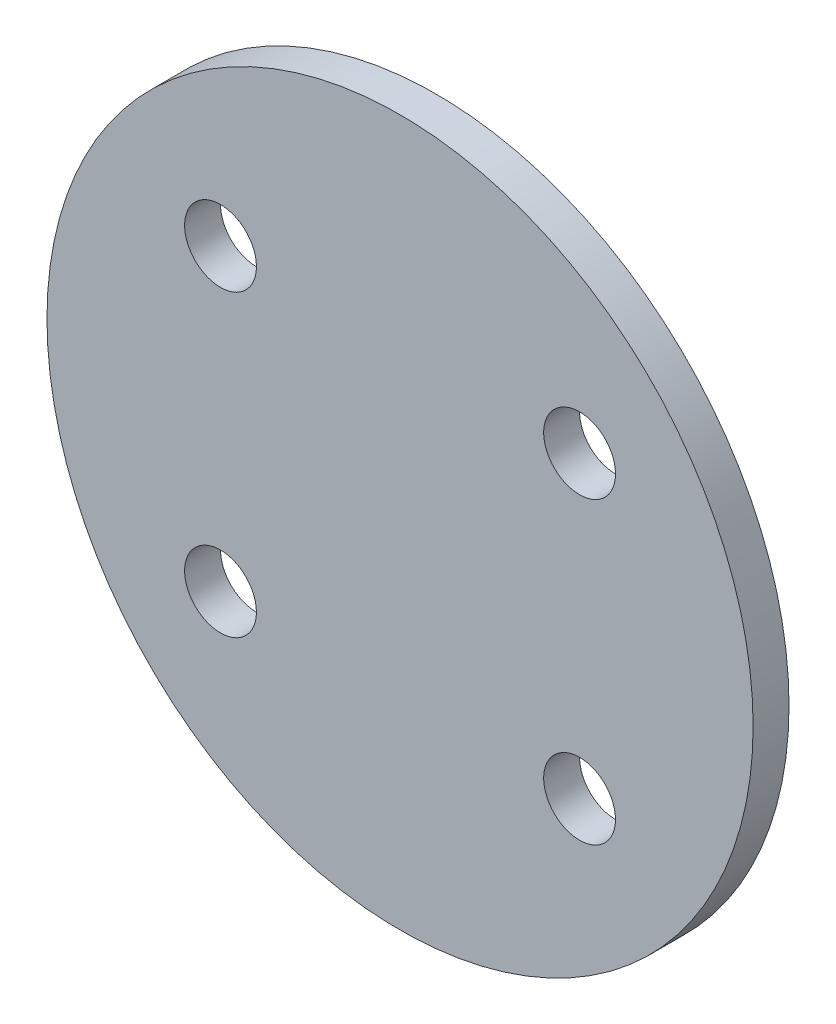
SolidWorks part; units mm, degrees
material "Acrylic (Medium-high impact)"
ref_plane "Front Plane" through (0, 0, 0) normal (0, 0, 1) x (1, 0, 0)
ref_plane "Top Plane" through (0, 0, 0) normal (0, 1, 0) x (1, 0, 0)
ref_plane "Right Plane" through (0, 0, 0) normal (1, 0, 0) x (0, 0, -1)
sketch "Model" plane through (0, 0, 0) normal (0, 0, 1) x (1, 0, 0)
  line L1 (15, -12.5) -> (-15, -12.5) construction
  line L2 (15, -12.5) -> (15, 12.5) construction
  line L3 (15, 12.5) -> (-15, 12.5) construction
  line L4 (-15, -12.5) -> (-15, 12.5) construction
  line L5 (15, -12.5) -> (-15, 12.5) construction
  line L6 (15, 12.5) -> (-15, -12.5) construction
  circle A0 centre (-15, -12.5) radius 3
  circle A1 centre (15, -12.5) radius 3
  circle A2 centre (15, 12.5) radius 3
  circle A7 centre (0, 0) radius 29.5
  circle A10 centre (-15, 12.5) radius 3
  dimension "D1" = 59
  dimension "D2" = 6
  dimension "D3" = 30
  dimension "D4" = 25
extrude "Boss-Extrude1" add sketch "Model" along normal blind 3
equation "\"D1@Model\"=58.80mm+\"cut_free@Parameters@FabricationParameters.sldprt\""
